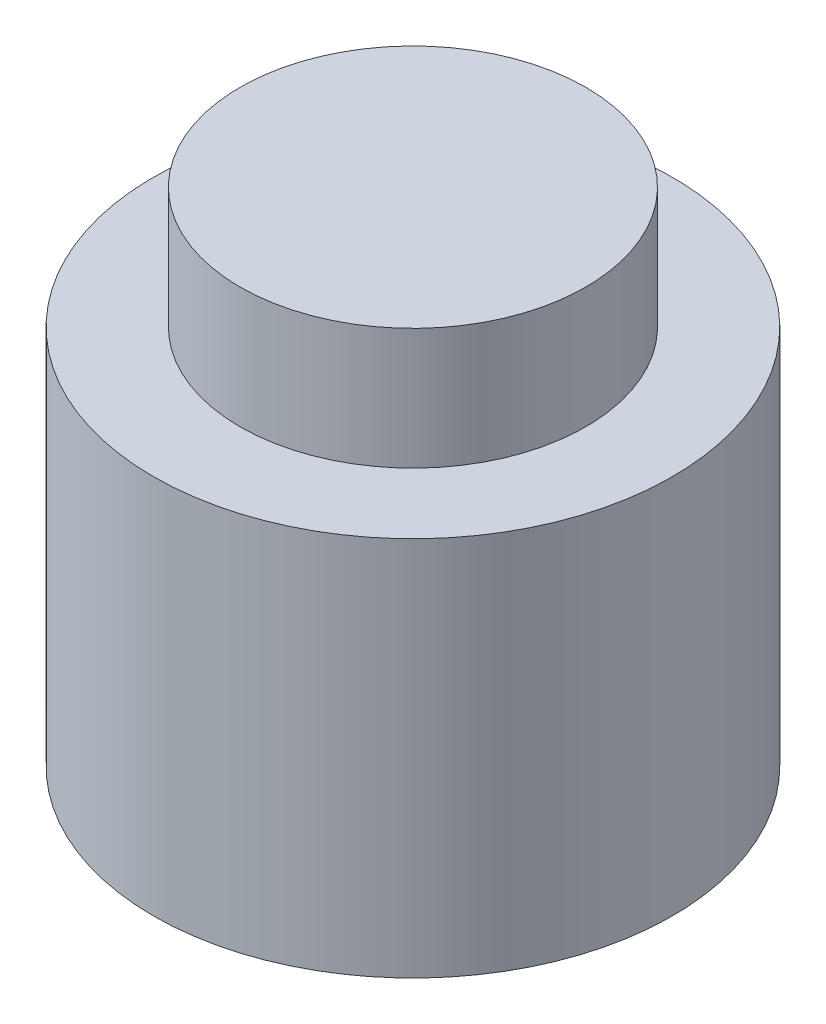
SolidWorks part; units mm, degrees
ref_plane "Front Plane" through (0, 0, 0) normal (0, 0, 1) x (1, 0, 0)
ref_plane "Top Plane" through (0, 0, 0) normal (0, 1, 0) x (1, 0, 0)
ref_plane "Right Plane" through (0, 0, 0) normal (1, 0, 0) x (0, 0, -1)
sketch "Sketch1" plane through (0, 0, 0) normal (0, 1, 0) x (1, 0, 0)
  circle A0 centre (0, 0) radius 15
  dimension "D1" = 30
extrude "Boss-Extrude1" add sketch "Sketch1" along normal blind 22
sketch "Sketch2" plane through (0, 22, 0) normal (0, 1, 0) x (1, 0, 0)
  circle A0 centre (0, 0) radius 10
  dimension "D1" = 20
extrude "Boss-Extrude2" add sketch "Sketch2" along normal blind 7
